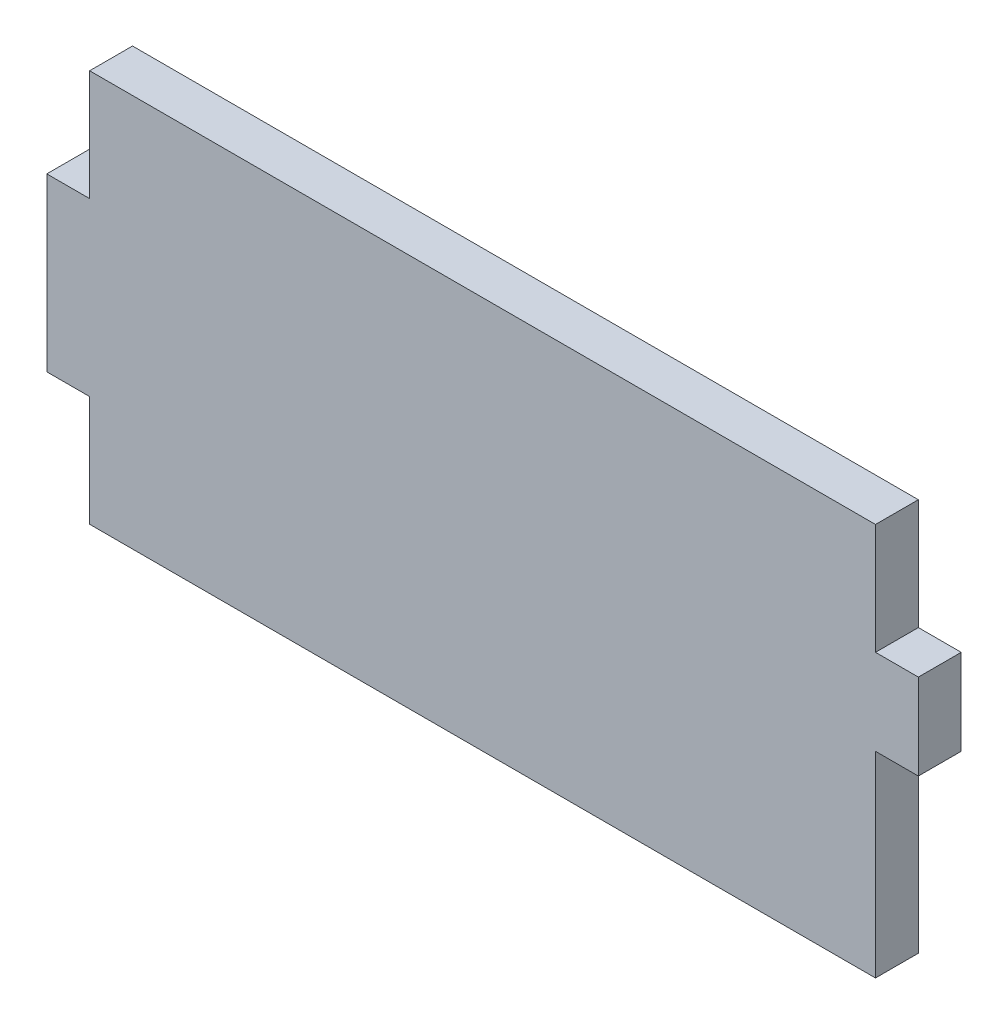
SolidWorks part; units mm, degrees
ref_plane "Přední rovina" through (0, 0, 0) normal (0, 0, 1) x (1, 0, 0)
ref_plane "Horní rovina" through (0, 0, 0) normal (0, 1, 0) x (1, 0, 0)
ref_plane "Pravá rovina" through (0, 0, 0) normal (1, 0, 0) x (0, 0, -1)
sketch "Skica1" plane through (0, 0, 0) normal (0, 0, 1) x (1, 0, 0)
  line L0 (55, -13.75) -> (55, -27.49)
  line L1 (0, 0) -> (55, 0)
  line L2 (0, 0) -> (0, -7.75)
  line L3 (0, -27.49) -> (55, -27.49)
  line L4 (55, 0) -> (55, -7.75)
  line L5 (0, -7.75) -> (-3, -7.75)
  line L6 (0, -19.75) -> (-3, -19.75)
  line L7 (-3, -7.75) -> (-3, -19.75)
  line L8 (55, -7.75) -> (58, -7.75)
  line L9 (55, -13.75) -> (58, -13.75)
  line L10 (58, -7.75) -> (58, -13.75)
  line L11 (0, -19.75) -> (0, -27.49)
  dimension "D1" = 55
  dimension "D2" = 27.49
  dimension "D3" = 7.75
  dimension "D4" = 0
  dimension "D5" = 6
  dimension "D6" = 12
  dimension "D7" = 3
  dimension "D8" = 3
extrude "Přidat vysunutím1" add sketch "Skica1" along normal blind 3
